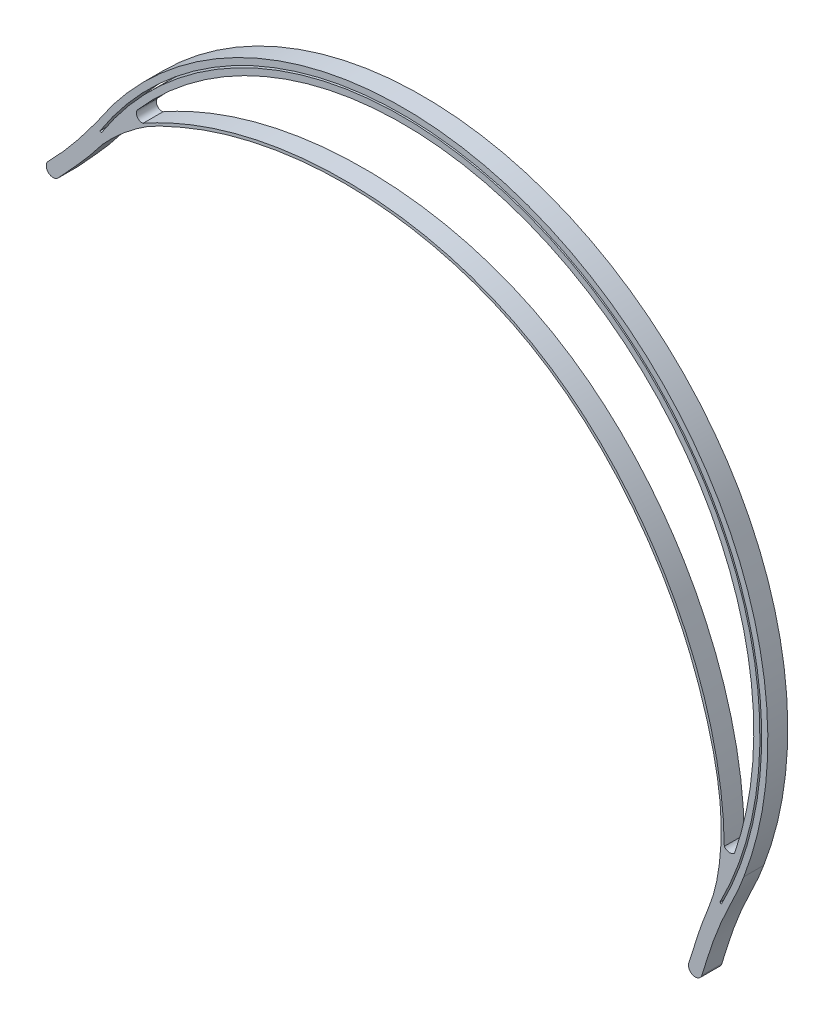
SolidWorks part; units mm, degrees
ref_plane "Front Plane" through (0, 0, 0) normal (0, 0, 1) x (1, 0, 0)
ref_plane "Top Plane" through (0, 0, 0) normal (0, 1, 0) x (1, 0, 0)
ref_plane "Right Plane" through (0, 0, 0) normal (1, 0, 0) x (0, 0, -1)
sketch "Sketch1" plane through (0, 0, 0) normal (0, 0, 1) x (1, 0, 0)
  line L0 (78.8602, -57.056) -> (78.4782, -56.8354)
  line L1 (-76.6822, 32.7462) -> (-77.0642, 32.9667)
  arc A0 (-73.7812, 40.3186) -> (84.4704, -48.3094) centre (-1.1493, -15.5906) cw
  arc A1 (78.8602, -57.056) -> (-77.0642, 32.9667) centre (-1.1492, -15.5905) ccw
  arc A2 (78.4782, -56.8354) -> (-76.6822, 32.7462) centre (-1.1492, -15.5905) ccw
  arc A3 (-67.6925, 42.1971) -> (82.168, -44.3248) centre (-1.1493, -15.5906) cw
  arc A4 (-67.5067, 42.4104) -> (-66.2242, 40.0563) centre (-66.499, 41.4329) ccw
  arc A5 (82.168, -44.3248) -> (79.5875, -44.1324) centre (80.958, -43.1517) cw
  arc A6 (70.7217, -73.8096) -> (73.9517, -74.9831) centre (72.3194, -74.444) ccw
  arc A7 (-90.0273, 19.882) -> (-87.5039, 17.542) centre (-88.788, 18.6878) ccw
  spline S0 degree 3 poles (-87.5039, 17.542) (-84.7078, 20.7632) (-80.8758, 24.4577) (-77.1009, 29.6773) (-74.8397, 32.0872) (-71.8515, 34.9868) (-68.714, 37.4902) (-64.2238, 40.5975) (-59.4525, 42.7685) (-54.3128, 44.9879) (-50.1625, 46.5168) (-41.703, 49.263) (-25.3179, 52.6557) (1.3284, 52.467) (24.5037, 44.9621) (38.3062, 35.8478) (43.8457, 31.4) (52.1628, 23.8319) (61.1232, 12.7993) (68.2152, -0.0701) (71.8277, -8.4934) (76.3359, -21.2811) (79.6903, -35.9315) (78.3722, -49.3266) (76.7989, -56.9962) (73.695, -63.6637) (71.8164, -70.5198) (70.7217, -73.8096) knots 0 0 0 0 0.048431 0.059754 0.072799 0.085754 0.106856 0.118129 0.147466 0.165856 0.181527 0.197481 0.266491 0.369825 0.496073 0.534749 0.556588 0.576398 0.66196 0.715661 0.742302 0.765538 0.869286 0.908166 0.916999 0.957616 1 1 1 1
  spline S1 degree 3 poles (-90.0273, 19.882) (-83.8742, 26.0717) (-78.6995, 33.1375) (-73.7812, 40.3186) knots 0 0 0 0 1 1 1 1
  spline S2 degree 3 poles (79.5875, -44.1324) (79.5355, -39.8907) (78.8522, -31.4075) (75.7104, -16.4441) (70.0855, -1.6799) (58.7334, 17.9957) (43.0331, 34.7996) (18.0868, 48.5558) (-13.7844, 55.3599) (-44.5589, 50.5921) (-62.2829, 42.2687) (-66.2242, 40.0563) knots 0 0 0 0 0.062629 0.125355 0.225242 0.294214 0.460411 0.556084 0.711355 0.933276 1 1 1 1
  spline S3 degree 3 poles (84.4704, -48.3094) (83.2553, -51.8113) (81.0229, -55.9697) (78.6974, -61.2071) (76.4966, -66.658) (75.1003, -71.3229) (73.9517, -74.9831) knots 0 0 0 0 0.385908 0.492308 0.598708 1 1 1 1
extrude "Boss-Extrude1" add sketch "Sketch1" along normal blind 5
sketch "Sketch2" plane through (0, 0, 0) normal (0, 0, -1) x (-1, 0, 0)
  line L0 (89.9582, 17.4258) -> (-71.7323, -76.0597) construction
  line L1 (34.8993, 112.6546) -> (-126.7913, 19.169)
  arc A1 (87.5039, 17.542) -> (90.0273, 19.882) centre (88.788, 18.6878) ccw construction
  arc A2 (-73.9517, -74.9831) -> (-70.7217, -73.8096) centre (-72.3194, -74.444) ccw construction
  dimension "D1" = 110
ref_plane "Plane1" through (38.7909, 67.1878, 0) normal (0.5, 0.866, 0) x (0, 0, -1)
ref_plane "Plane2" through (41.2909, 71.518, 0) normal (0.5, 0.866, 0) x (0, 0, -1)
sketch "Sketch4" plane through (0, 0, 0) normal (0, 0, -1) x (-1, 0, 0)
  line L0 (44.0904, -62.1451) -> (-72.8857, 102.7317) construction
  arc A0 (67.5067, 42.4104) -> (-82.168, -44.3248) centre (1.1493, -15.5906) ccw construction
  point P2 (-43.0396, 60.664)
sketch "Sketch5" plane through (0, 0, 5) normal (0, 0, 1) x (1, 0, 0)
  line L0 (55.2201, 77.8322) -> (-8.4146, -11.8604) construction
  line L1 (-44.0904, -62.1451) -> (72.8857, 102.7317) construction
ref_plane "Plane3" through (0, 0, 0) normal (0.8156, -0.5786, 0) x (0, 0, -1)
sketch "Sketch6" plane through (0, 0, 0) normal (0.8156, -0.5786, 0) x (0, 0, -1)
  line L0 (-0.5, 145.1584) -> (-0.5, -57.8824) construction
  line L1 (-5, 9.4773) -> (-5, -18.3639) construction
  line L2 (6.3067, -27.9816) -> (-18.3539, -27.9816) construction
  circle A0 centre (-0.5, -27.9816) radius 1.5
  dimension "D2" = 3
  dimension "D1" = 4.5
sketch "Sketch7" plane through (0, 0, 0) normal (0.8156, -0.5786, 0) x (0, 0, -1)
  line L0 (0, -76.197) -> (0, 125.9608) construction
  circle A0 centre (-5, -12.0782) radius 1.5
  dimension "D1" = 3
  dimension "D2" = 5
